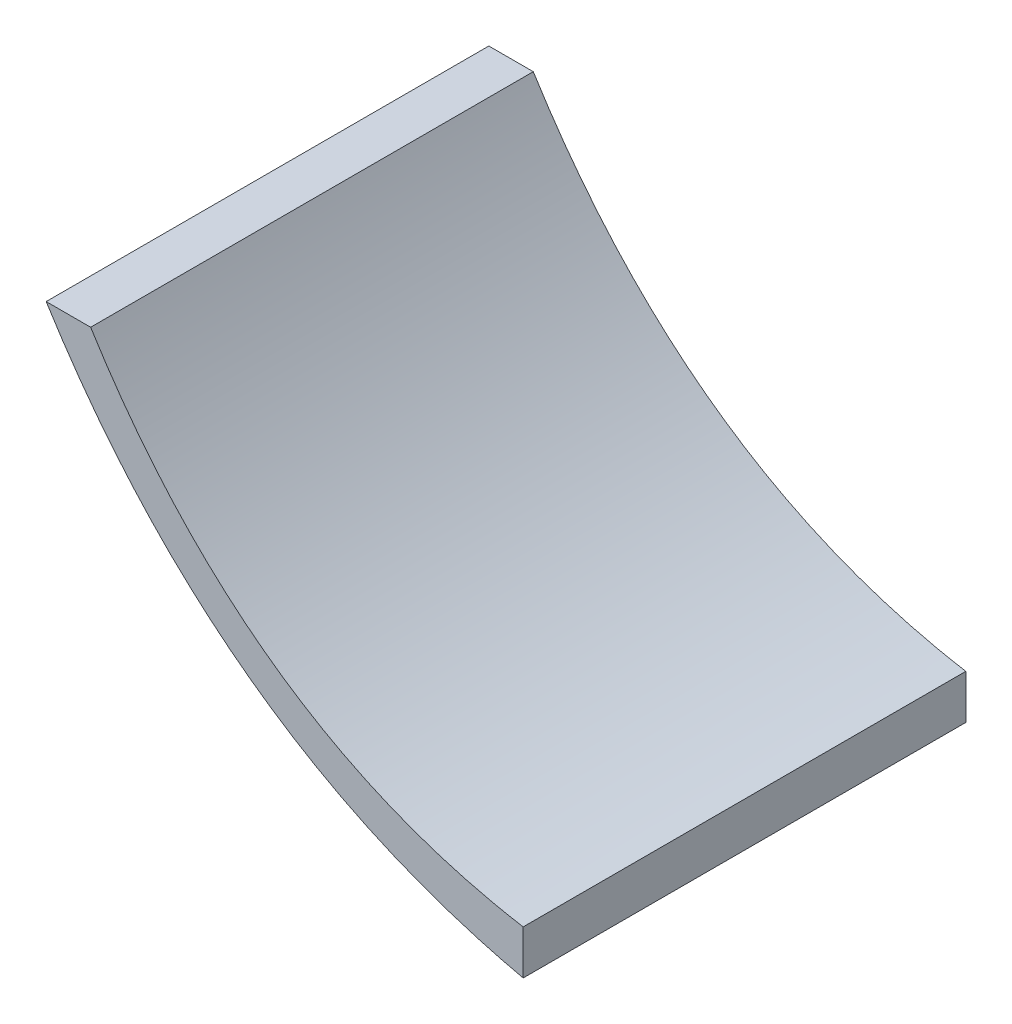
SolidWorks part; units mm, degrees
material "ALUMINUM 6061-T6"
ref_plane "Front Plane" through (0, 0, 0) normal (0, 0, 1) x (1, 0, 0)
ref_plane "Top Plane" through (0, 0, 0) normal (0, 1, 0) x (1, 0, 0)
ref_plane "Right Plane" through (0, 0, 0) normal (1, 0, 0) x (0, 0, -1)
sketch "Sketch1" plane through (0, 0, 0) normal (0, 0, 1) x (1, 0, 0)
  line L0 (-124.1009, 84.2638) -> (-136.8575, 84.2638)
  line L1 (0, -15.3818) -> (0, -2.6818)
  spline S0 degree 2 poles (-124.1009, 84.2638) (-78.317, 10.658) (0, -2.6818) knots 0 0 0 1 1 1
  spline S1 degree 2 poles (-136.8575, 84.2638) (-86.8571, 4.1264) (0, -15.3818) knots 0 0 0 1 1 1
extrude "Boss-Extrude1" add sketch "Sketch1" along normal mid plane 127 contours S0 L1 S1 L0
